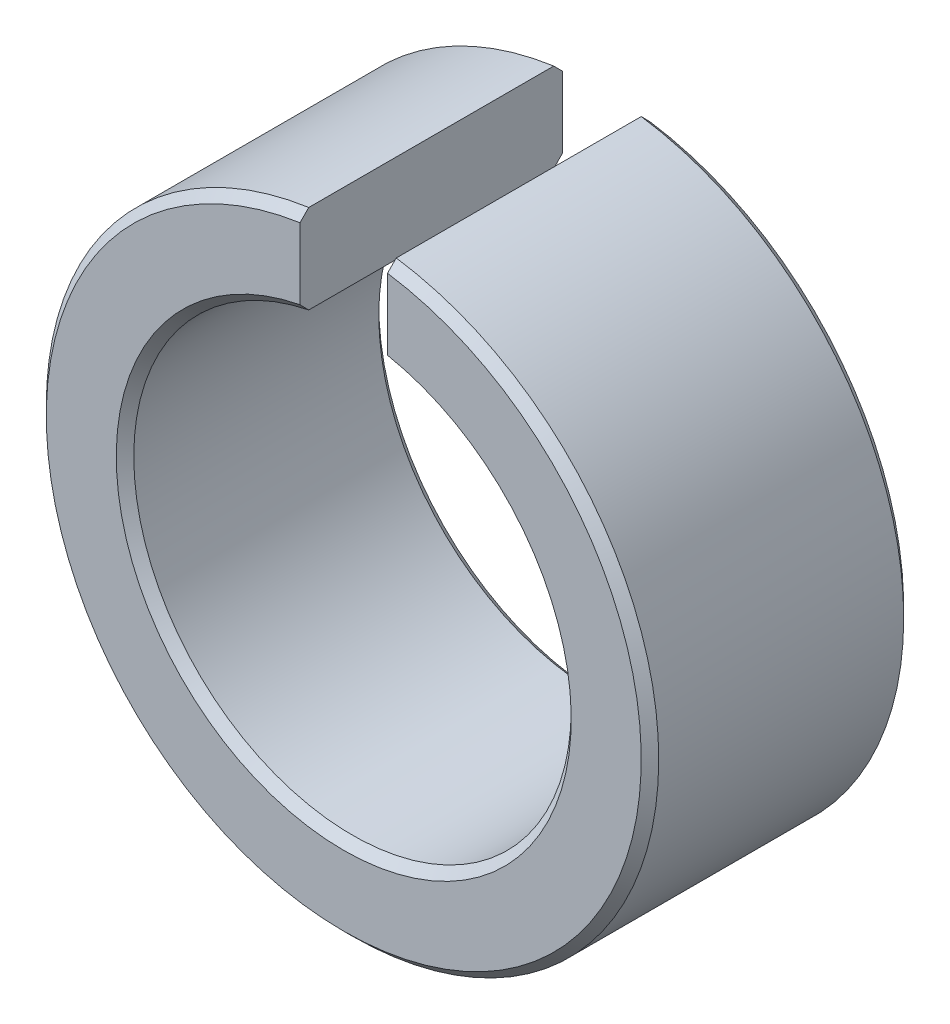
SolidWorks part; units mm, degrees
ref_plane "前视基准面" through (0, 0, 0) normal (0, 0, 1) x (1, 0, 0)
ref_plane "上视基准面" through (0, 0, 0) normal (0, 1, 0) x (1, 0, 0)
ref_plane "右视基准面" through (0, 0, 0) normal (1, 0, 0) x (0, 0, -1)
other "Configuration Table"
sketch "草图1" plane through (0, 0, 0) normal (0, 0, 1) x (1, 0, 0)
  circle A0 centre (0, 0) radius 2.5
  dimension "D1" = 5
extrude "拉伸-薄壁1" add sketch "草图1" along normal blind 3 thin
chamfer "倒角1" distance 0.1 angle 45 4 edges at (2.5, 0, 0) (2.5, 0, 3) (3.5, 0, 0) (3.5, 0, 3)
sketch "草图2" plane through (0, 0, 0) normal (0, 0, -1) x (-1, 0, 0)
  line L0 (0, 0) -> (0, 3.5)
  circle A1 centre (0, 0) radius 3.5 construction
extrude "切除-拉伸-薄壁2" cut sketch "草图2" against normal through all and the other way through all thin thin type mid plane wall 1
